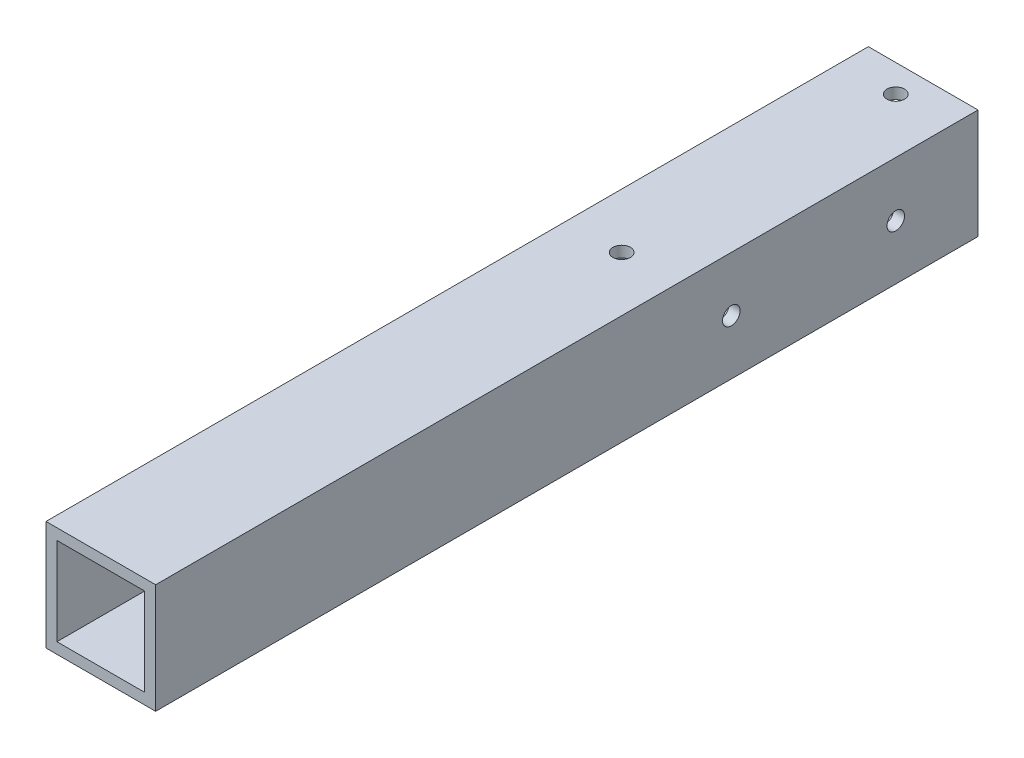
SolidWorks part; units mm, degrees
ref_plane "正面" through (0, 0, 0) normal (0, 0, 1) x (1, 0, 0)
ref_plane "平面" through (0, 0, 0) normal (0, 1, 0) x (1, 0, 0)
ref_plane "右側面" through (0, 0, 0) normal (1, 0, 0) x (0, 0, -1)
sketch "ｽｹｯﾁ1" plane through (0, 0, 0) normal (0, 0, 1) x (1, 0, 0)
  line L0 (-8, 8) -> (-8, -8)
  line L1 (-10, 10) -> (10, 10)
  line L2 (-10, 10) -> (-10, -10)
  line L3 (-10, -10) -> (10, -10)
  line L4 (10, 10) -> (10, -10)
  line L5 (-10, 10) -> (10, -10) construction
  line L6 (-10, -10) -> (10, 10) construction
  line L7 (-8, -8) -> (8, -8)
  line L8 (8, 8) -> (8, -8)
  line L9 (-8, 8) -> (8, 8)
  point P0 (0, 0)
  dimension "D1" = 20
  dimension "D2" = 20
  dimension "D3" = 2
extrude "ﾎﾞｽ - 押し出し1" add sketch "ｽｹｯﾁ1" along normal blind 150
sketch "ｽｹｯﾁ2" plane through (0, 10, 0) normal (0, 1, 0) x (1, 0, 0)
  line L1 (10, 0) -> (-10, 0) construction
  circle A0 centre (0, -5) radius 1.6
  circle A1 centre (0, -55) radius 1.6
  dimension "D1" = 55
  dimension "D2" = 3.2
  dimension "D3" = 5
  dimension "D4" = 3.2
extrude "ｶｯﾄ - 押し出し1" cut sketch "ｽｹｯﾁ2" against normal blind 408.3717
sketch "ｽｹｯﾁ3" plane through (10, 0, 0) normal (1, 0, 0) x (0, 0, -1)
  line L1 (0, -10) -> (0, 10) construction
  circle A0 centre (-15, 0) radius 1.6
  circle A1 centre (-45, 0) radius 1.6
  dimension "D1" = 3.2
  dimension "D2" = 3.2
  dimension "D3" = 45
  dimension "D4" = 15
extrude "ｶｯﾄ - 押し出し2" cut sketch "ｽｹｯﾁ3" against normal blind 10
